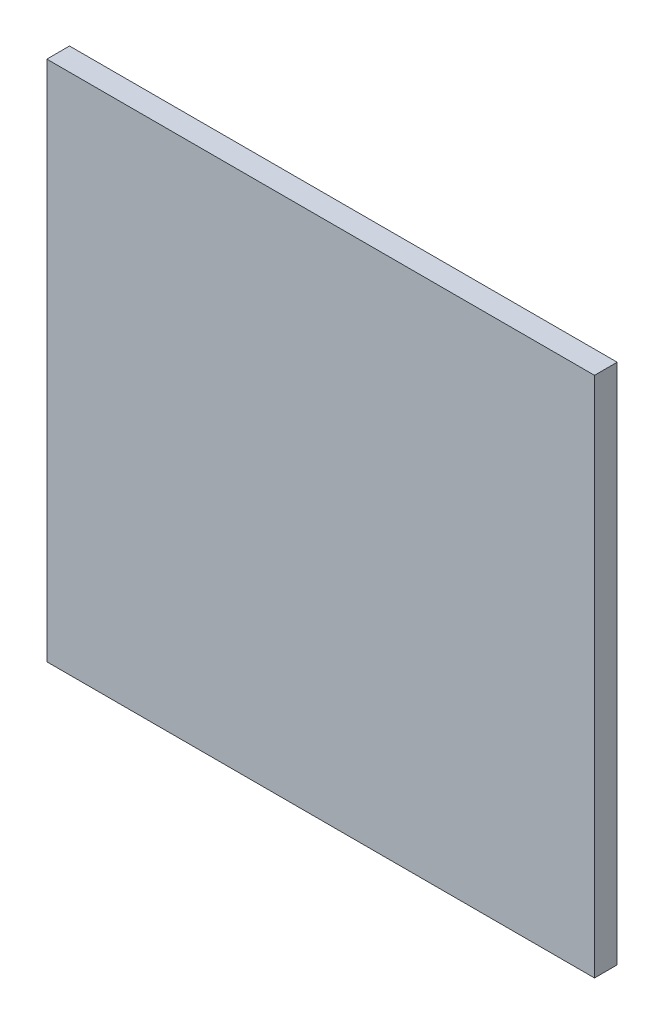
SolidWorks part; units mm, degrees
ref_plane "前视基准面" through (0, 0, 0) normal (0, 0, 1) x (1, 0, 0)
ref_plane "上视基准面" through (0, 0, 0) normal (0, 1, 0) x (1, 0, 0)
ref_plane "右视基准面" through (0, 0, 0) normal (1, 0, 0) x (0, 0, -1)
sketch "草图1" plane through (0, 0, 0) normal (0, 0, 1) x (1, 0, 0)
  line L1 (-18.1, 17.25) -> (18.1, 17.25)
  line L2 (-18.1, 17.25) -> (-18.1, -17.25)
  line L3 (-18.1, -17.25) -> (18.1, -17.25)
  line L4 (18.1, 17.25) -> (18.1, -17.25)
  line L5 (-18.1, 17.25) -> (18.1, -17.25) construction
  line L6 (-18.1, -17.25) -> (18.1, 17.25) construction
  point P0 (0, 0)
  dimension "D1" = 36.2
  dimension "D2" = 34.5
extrude "凸台-拉伸1" add sketch "草图1" along normal blind 1.5
